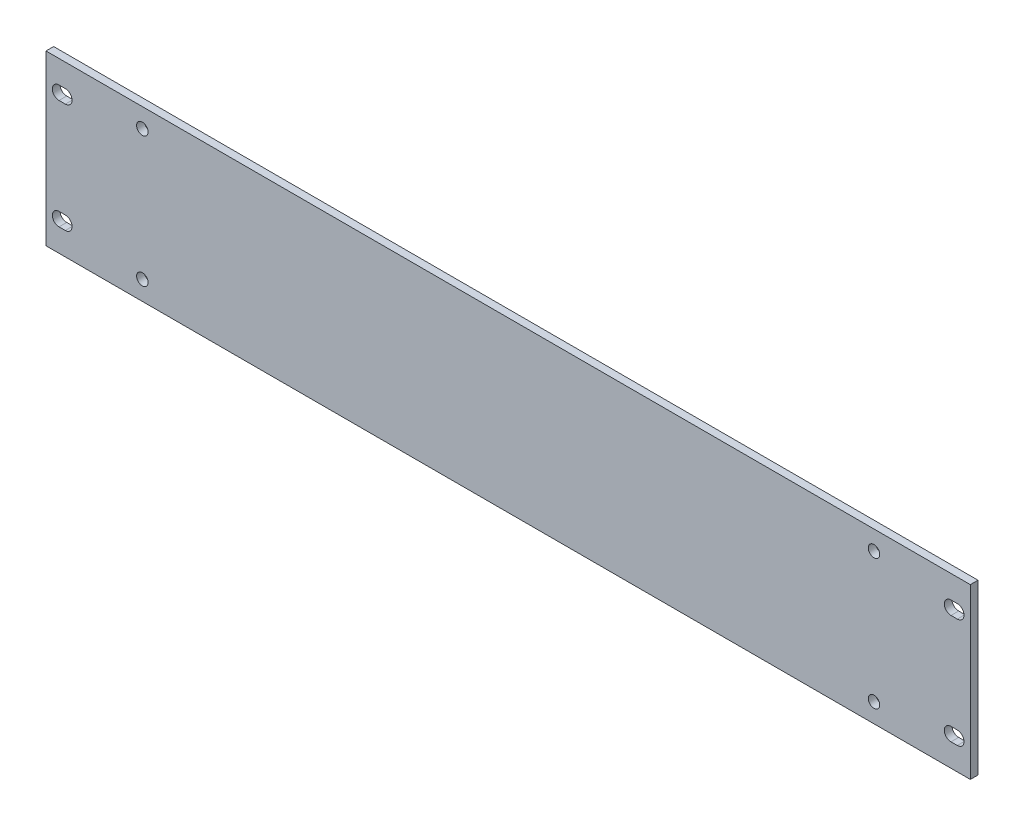
SolidWorks part; units mm, degrees
material "1060 Сплав"
ref_plane "Front" through (0, 0, 0) normal (0, 0, 1) x (1, 0, 0)
ref_plane "Top" through (0, 0, 0) normal (0, 1, 0) x (1, 0, 0)
ref_plane "Right" through (0, 0, 0) normal (1, 0, 0) x (0, 0, -1)
sketch "Эскиз1" plane through (0, 0, 0) normal (0, 0, 1) x (1, 0, 0)
  line L1 (0, 0) -> (482.6, 0)
  line L2 (0, 0) -> (0, 88.1)
  line L3 (0, 88.1) -> (482.6, 88.1)
  line L4 (482.6, 0) -> (482.6, 88.1)
  dimension "D1" = 88.1
  dimension "D2" = 482.6
extrude "Бобышка-Вытянуть1" add sketch "Эскиз1" along normal blind 4
sketch "Эскиз2" plane through (0, 0, 4) normal (0, 0, 1) x (1, 0, 0)
  line L0 (6.8, 72.62) -> (10.1, 72.62) construction
  line L1 (6.8, 76.12) -> (10.1, 76.12)
  line L2 (6.8, 69.12) -> (10.1, 69.12)
  line L3 (0, 88.1) -> (0, 0) construction
  line L4 (482.6, 88.1) -> (0, 88.1) construction
  line L5 (472.5, 72.62) -> (475.8, 72.62) construction
  line L6 (472.5, 76.12) -> (475.8, 76.12)
  line L7 (472.5, 69.12) -> (475.8, 69.12)
  line L8 (472.5, 15.47) -> (475.8, 15.47) construction
  line L9 (472.5, 18.97) -> (475.8, 18.97)
  line L10 (472.5, 11.97) -> (475.8, 11.97)
  line L11 (6.8, 15.47) -> (10.1, 15.47) construction
  line L12 (6.8, 18.97) -> (10.1, 18.97)
  line L13 (6.8, 11.97) -> (10.1, 11.97)
  line L15 (482.6, 0) -> (482.6, 88.1) construction
  arc A0 (6.8, 76.12) -> (6.8, 69.12) centre (6.8, 72.62) ccw
  arc A1 (10.1, 69.12) -> (10.1, 76.12) centre (10.1, 72.62) ccw
  arc A2 (472.5, 76.12) -> (472.5, 69.12) centre (472.5, 72.62) ccw
  arc A3 (475.8, 69.12) -> (475.8, 76.12) centre (475.8, 72.62) ccw
  arc A4 (472.5, 18.97) -> (472.5, 11.97) centre (472.5, 15.47) ccw
  arc A5 (475.8, 11.97) -> (475.8, 18.97) centre (475.8, 15.47) ccw
  arc A6 (6.8, 18.97) -> (6.8, 11.97) centre (6.8, 15.47) ccw
  arc A7 (10.1, 11.97) -> (10.1, 18.97) centre (10.1, 15.47) ccw
  point P2 (8.45, 72.62)
  point P16 (474.15, 72.62)
  point P23 (474.15, 15.47)
  point P30 (8.45, 15.47)
  dimension "D2" = 3.5
  dimension "D4" = 15.48
  dimension "D7" = 6.8
  dimension "D1" = 3.3
  dimension "D3" = 6.8
  dimension "D5" = 2
  dimension "D6" = 2
extrude "Вырез-Вытянуть1" cut sketch "Эскиз2" against normal through all
sketch "Эскиз3" plane through (0, 0, 4) normal (0, 0, 1) x (1, 0, 0)
  line L0 (0, 88.1) -> (0, 0) construction
  line L1 (482.6, 88.1) -> (0, 88.1) construction
  line L2 (0, 0) -> (482.6, 0) construction
  line L3 (482.6, 0) -> (482.6, 88.1) construction
  circle A0 centre (50.3, 78.1) radius 3
  circle A1 centre (432.3, 78.1) radius 3
  circle A2 centre (432.3, 10) radius 3
  circle A3 centre (50.3, 10) radius 3
  dimension "D1" = 6
  dimension "D2" = 50.3
  dimension "D3" = 10
  dimension "D6" = 10
  dimension "D7" = 50.3
  dimension "D4" = 2
  dimension "D5" = 2
extrude "Вырез-Вытянуть2" cut sketch "Эскиз3" against normal through all
